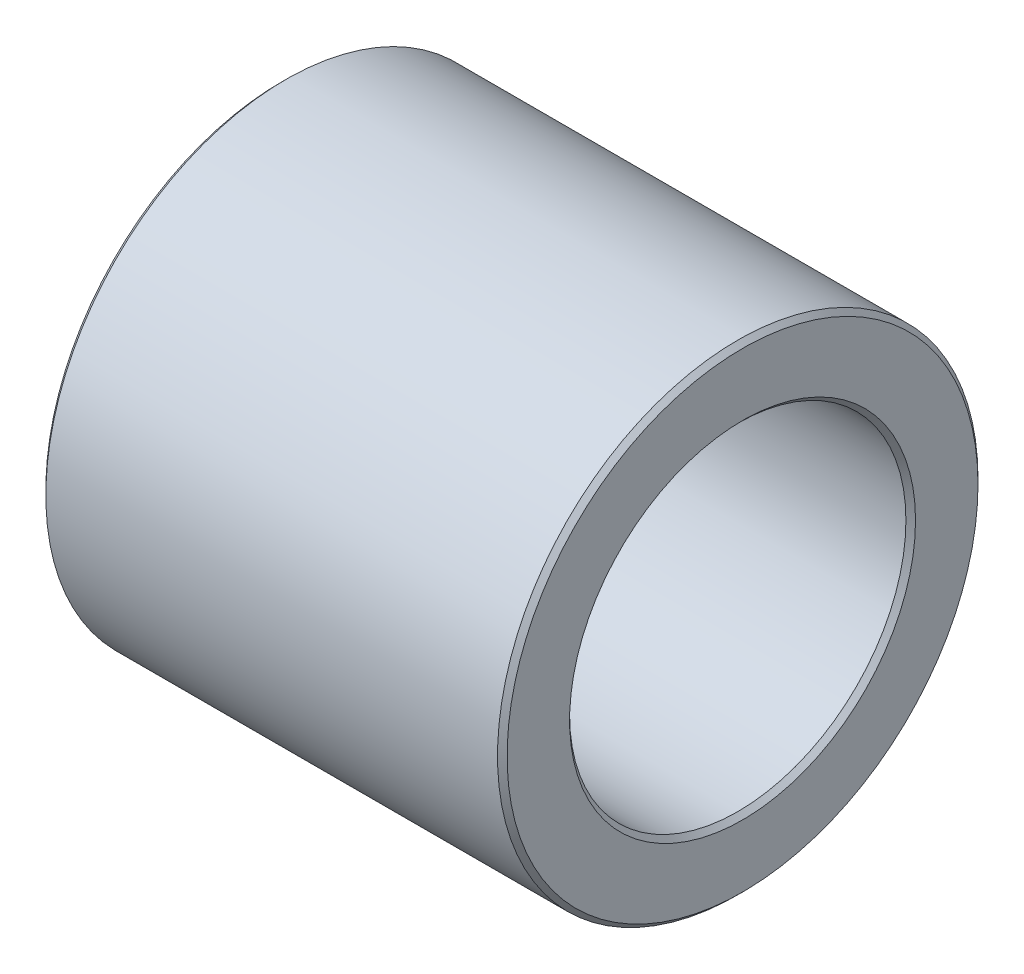
SolidWorks part; units mm, degrees
material "20"
ref_plane "前视基准面" through (0, 0, 0) normal (0, 0, 1) x (1, 0, 0)
ref_plane "上视基准面" through (0, 0, 0) normal (0, 1, 0) x (1, 0, 0)
ref_plane "右视基准面" through (0, 0, 0) normal (1, 0, 0) x (0, 0, -1)
sketch "草图1" plane through (0, 0, 0) normal (1, 0, 0) x (0, 0, -1)
  circle A0 centre (0, 0) radius 50
  circle A1 centre (0, 0) radius 35
  dimension "D1" = 100
  dimension "D2" = 70
extrude "凸台-拉伸1" add sketch "草图1" along normal blind 96
chamfer "倒角1" distance 1 angle 45 4 edges at (96, 0, -35) (96, 0, -50) (0, 0, -35) (0, 0, -50)
